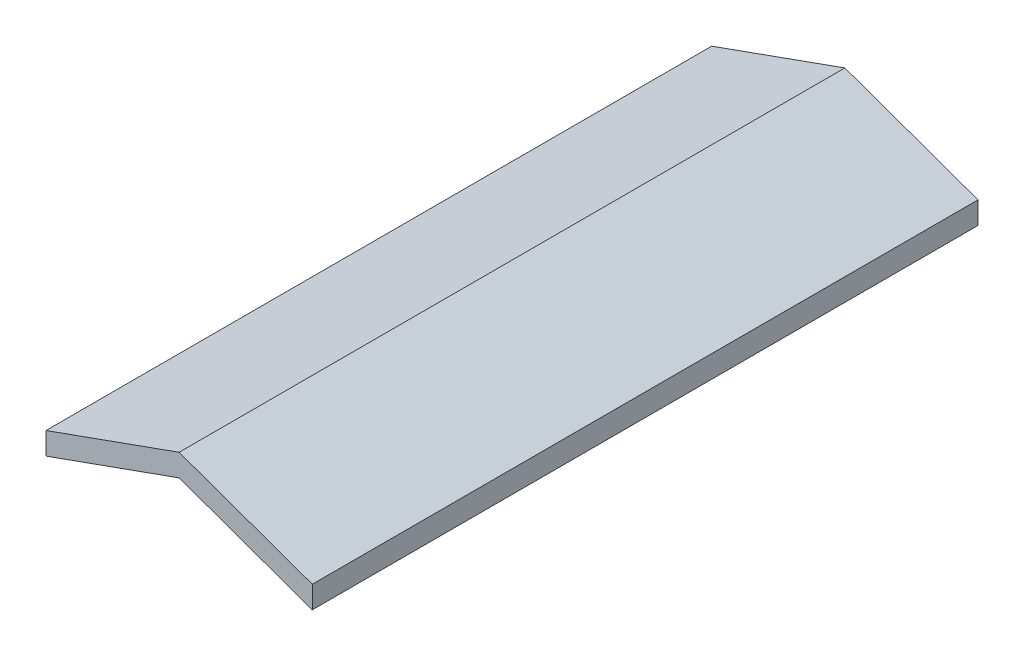
SolidWorks part; units mm, degrees
ref_plane "正面" through (0, 0, 0) normal (0, 0, 1) x (1, 0, 0)
ref_plane "平面" through (0, 0, 0) normal (0, 1, 0) x (1, 0, 0)
ref_plane "右側面" through (0, 0, 0) normal (1, 0, 0) x (0, 0, -1)
sketch "ｽｹｯﾁ1" plane through (0, 0, 0) normal (0, 0, 1) x (1, 0, 0)
  line L0 (0, 0) -> (-6000, -2150)
  line L1 (-6000, -2150) -> (-6000, -3150)
  line L2 (-6000, -3150) -> (0, -1000)
  line L3 (0, -1000) -> (6000, -3150)
  line L4 (6000, -3150) -> (6000, -2150)
  line L5 (6000, -2150) -> (0, 0)
  dimension "D1" = 1000
  dimension "D2" = 12000
  dimension "D3" = 1000
  dimension "D4" = 6000
  dimension "D5" = 6000
  dimension "D6" = 1000
  dimension "D7" = 2150
  dimension "D8" = 2150
extrude "ﾎﾞｽ - 押し出し1" add sketch "ｽｹｯﾁ1" along normal blind 30000
